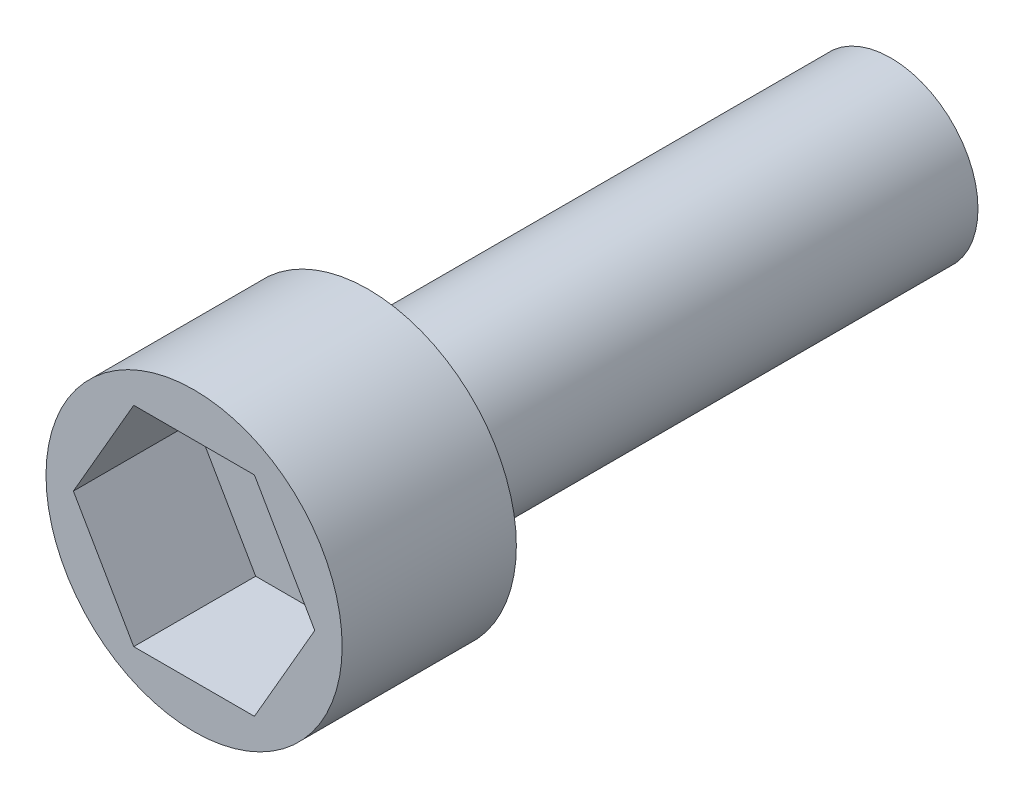
SolidWorks part; units mm, degrees
ref_plane "Plan de face" through (0, 0, 0) normal (0, 0, 1) x (1, 0, 0)
ref_plane "Plan de dessus" through (0, 0, 0) normal (0, 1, 0) x (1, 0, 0)
ref_plane "Plan de droite" through (0, 0, 0) normal (1, 0, 0) x (0, 0, -1)
sketch "Esquisse1" plane through (0, 0, 0) normal (0, 0, 1) x (1, 0, 0)
  circle A0 centre (0, 0) radius 2.5
  dimension "D1" = 5
extrude "Boss.-Extru.1" add sketch "Esquisse1" along normal blind 15
sketch "Esquisse2" plane through (0, 0, 15) normal (0, 0, 1) x (1, 0, 0)
  circle A0 centre (0, 0) radius 4.25
  dimension "D1" = 8.5
extrude "Boss.-Extru.2" add sketch "Esquisse2" along normal blind 5
sketch "Esquisse3" plane through (0, 0, 20) normal (0, 0, 1) x (1, 0, 0)
  line L1 (3.4641, 0) -> (1.7321, 3)
  line L2 (1.7321, 3) -> (-1.7321, 3)
  line L3 (-1.7321, 3) -> (-3.4641, 0)
  line L4 (-3.4641, 0) -> (-1.7321, -3)
  line L5 (-1.7321, -3) -> (1.7321, -3)
  line L6 (1.7321, -3) -> (3.4641, 0)
  circle A0 centre (0, 0) radius 3 construction
  dimension "D1" = 6
extrude "Enlèv. mat.-Extru.1" cut sketch "Esquisse3" against normal blind 3.5
